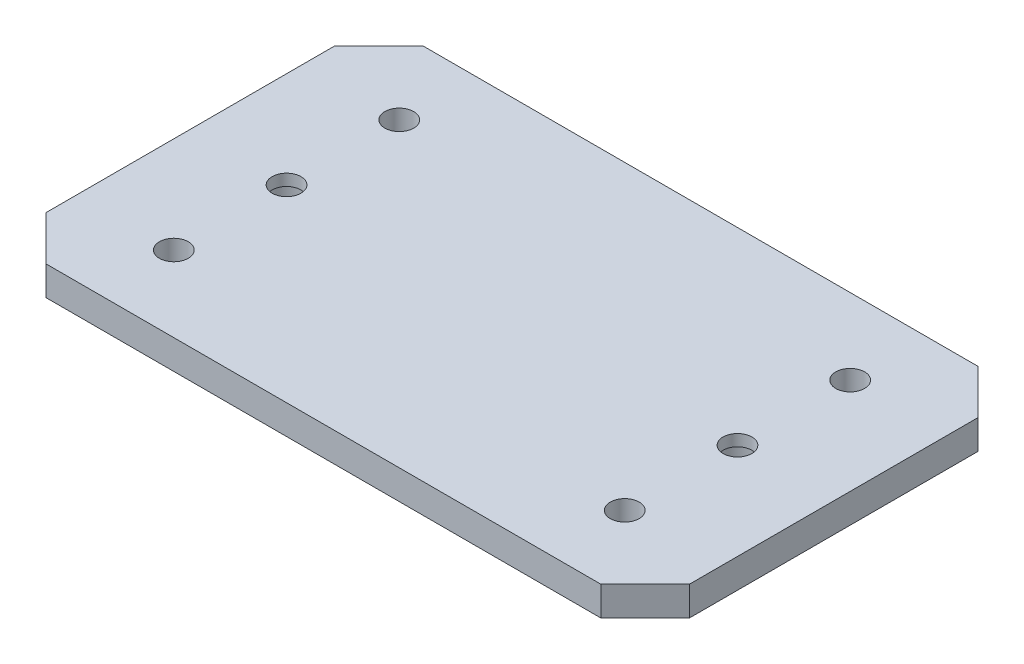
SolidWorks part; units mm, degrees
ref_plane "Front Plane" through (0, 0, 0) normal (0, 0, 1) x (1, 0, 0)
ref_plane "Top Plane" through (0, 0, 0) normal (0, 1, 0) x (1, 0, 0)
ref_plane "Right Plane" through (0, 0, 0) normal (1, 0, 0) x (0, 0, -1)
sketch "Sketch1" plane through (0, 0, 0) normal (0, 1, 0) x (1, 0, 0)
  line L1 (-72.5, -42.5) -> (72.5, -42.5)
  line L2 (-72.5, -42.5) -> (-72.5, 42.5)
  line L3 (-72.5, 42.5) -> (72.5, 42.5)
  line L4 (72.5, -42.5) -> (72.5, 42.5)
  line L5 (-72.5, -42.5) -> (72.5, 42.5) construction
  line L6 (-72.5, 42.5) -> (72.5, -42.5) construction
  point P0 (0, 0)
  dimension "D1" = 145
  dimension "D2" = 85
extrude "Boss-Extrude1" add sketch "Sketch1" along normal blind 6.6
sketch "Sketch2" plane through (0, 6.6, 0) normal (0, 1, 0) x (1, 0, 0)
  line L1 (50.8, 25.4) -> (-50.8, 25.4) construction
  line L2 (50.8, 25.4) -> (50.8, -25.4) construction
  line L3 (50.8, -25.4) -> (-50.8, -25.4) construction
  line L4 (-50.8, 25.4) -> (-50.8, -25.4) construction
  line L5 (50.8, 25.4) -> (-50.8, -25.4) construction
  line L6 (50.8, -25.4) -> (-50.8, 25.4) construction
  line L7 (0, 0) -> (0, 25.4) construction
  circle A0 centre (-50.8, 25.4) radius 3.25
  circle A1 centre (50.8, 25.4) radius 3.25
  circle A2 centre (50.8, -25.4) radius 3.25
  circle A3 centre (-50.8, -25.4) radius 3.25
  circle A4 centre (50.8, 0) radius 3.25
  circle A5 centre (-50.8, 0) radius 3.25
  point P0 (0, 0)
  dimension "D3" = 6.5
  dimension "D6" = 6.5
  dimension "D1" = 50.8
  dimension "D2" = 101.6
  dimension "D4" = 2
  dimension "D5" = 2
extrude "Cut-Extrude1" cut sketch "Sketch2" against normal through all
chamfer "Chamfer1" distance 10 angle 45 4 edges at (72.5, 3.3, -42.5) (72.5, 3.3, 42.5) (-72.5, 3.3, 42.5) (-72.5, 3.3, -42.5)
sketch "Sketch3" plane through (0, 0, 0) normal (0, -1, 0) x (1, 0, 0)
  circle A0 centre (50.8, 0) radius 3.25 construction
  circle A1 centre (-50.8, 0) radius 3.25 construction
  circle A2 centre (50.8, 0) radius 3.25
  circle A3 centre (-50.8, 0) radius 3.25
  circle A4 centre (50.8, 0) radius 5.25
  circle A5 centre (-50.8, 0) radius 5.25
  circle M3 centre (50.8, 0) radius 3.25
  circle M7 centre (-50.8, 0) radius 3.25
  dimension "D1" = 2
extrude "Cut-Extrude2" cut sketch "Sketch3" against normal blind 4 contours A4 M3 | A5 M7
ref_point "Point1"
sketch "Sketch4" plane through (0, 0, 0) normal (0, -1, 0) x (1, 0, 0)
  line L8 (-62.5, -42.5) -> (62.5, -42.5)
  line L9 (62.5, -42.5) -> (72.5, -32.5)
  line L10 (72.5, -32.5) -> (72.5, 32.5)
  line L11 (72.5, 32.5) -> (62.5, 42.5)
  line L12 (62.5, 42.5) -> (-62.5, 42.5)
  line L13 (-62.5, 42.5) -> (-72.5, 32.5)
  line L14 (-72.5, 32.5) -> (-72.5, -32.5)
  line L15 (-72.5, -32.5) -> (-62.5, -42.5)
  line L16 (-62.5, -42.5) -> (62.5, -42.5)
  line L17 (62.5, -42.5) -> (72.5, -32.5)
  line L18 (72.5, -32.5) -> (72.5, 32.5)
  line L19 (72.5, 32.5) -> (62.5, 42.5)
  line L20 (62.5, 42.5) -> (-62.5, 42.5)
  line L21 (-62.5, 42.5) -> (-72.5, 32.5)
  line L22 (-72.5, 32.5) -> (-72.5, -32.5)
  line L23 (-72.5, -32.5) -> (-62.5, -42.5)
  circle A1 centre (-25.4, 25.4) radius 2.25
  circle A2 centre (-50.8, 25.4) radius 2.25
  circle A3 centre (-50.8, 25.4) radius 2.25
  circle A4 centre (0, 25.4) radius 2.25
  circle A5 centre (25.4, 25.4) radius 2.25
  circle A6 centre (-25.4, 0) radius 2.25
  circle A7 centre (0, 0) radius 2.25
  circle A8 centre (25.4, 0) radius 2.25
  circle A9 centre (-25.4, -25.4) radius 2.25
  circle A10 centre (0, -25.4) radius 2.25
  circle A11 centre (25.4, -25.4) radius 2.25
  circle A12 centre (-50.8, 0) radius 2.25
  circle A13 centre (-50.8, -25.4) radius 2.25
  dimension "D1" = 0
  dimension "D2" = 1
  dimension "D3" = 4
  dimension "D4" = 3
extrude "Cut-Extrude3" cut sketch "Sketch4" against normal blind 1.5 contours A1 | A6 | A9 | A10 | A7 | A4 | A5 | A8 | A11
